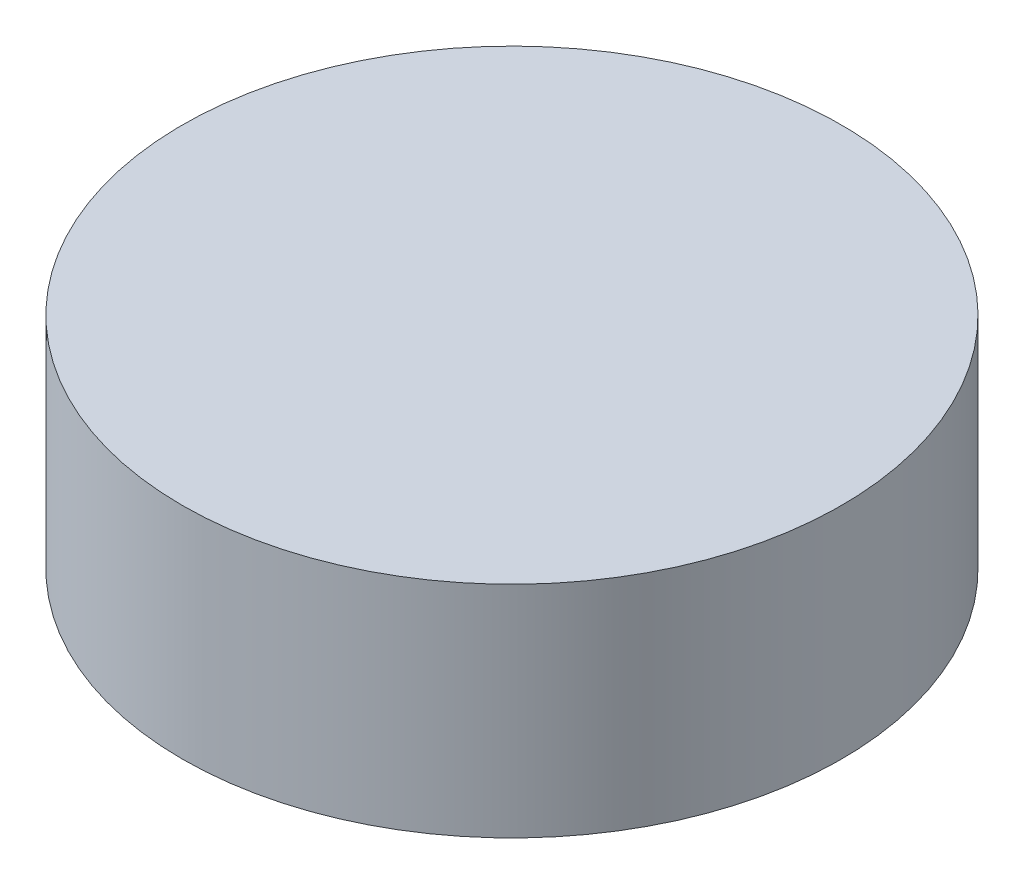
SolidWorks part; units mm, degrees
ref_plane "Front Plane" through (0, 0, 0) normal (0, 0, 1) x (1, 0, 0)
ref_plane "Top Plane" through (0, 0, 0) normal (0, 1, 0) x (1, 0, 0)
ref_plane "Right Plane" through (0, 0, 0) normal (1, 0, 0) x (0, 0, -1)
sketch "Sketch1" plane through (0, 0, 0) normal (0, 1, 0) x (1, 0, 0)
  circle A0 centre (0, 0) radius 7.5
  dimension "D1" = 15
extrude "Boss-Extrude1" add sketch "Sketch1" along normal blind 5
